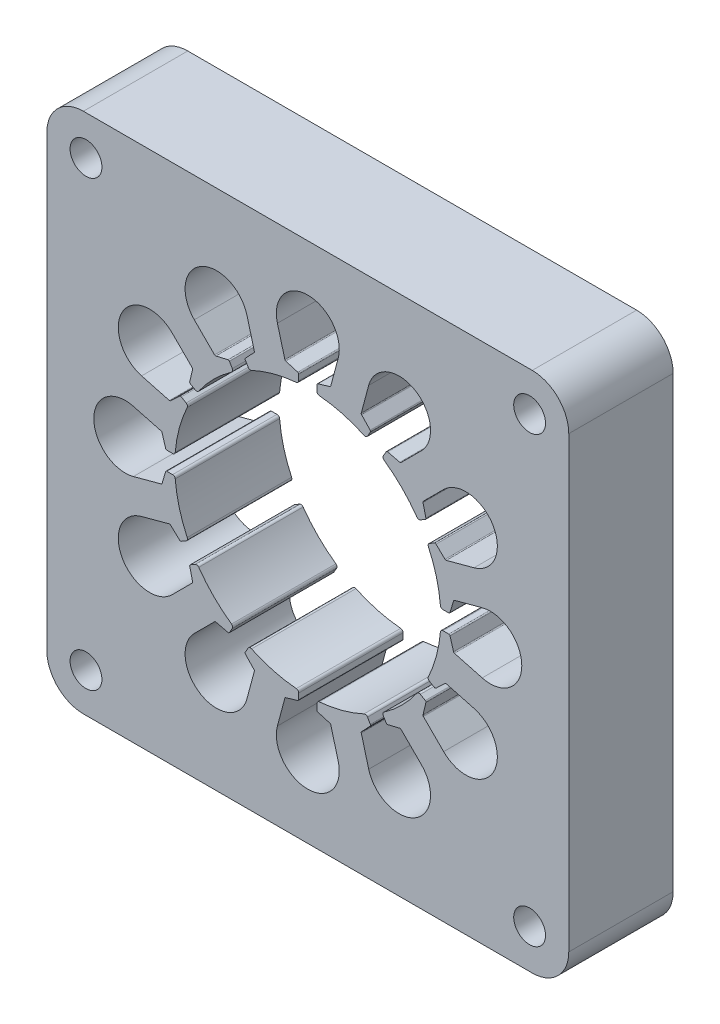
SolidWorks part; units mm, degrees
ref_plane "Front" through (0, 0, 0) normal (0, 0, 1) x (1, 0, 0)
ref_plane "Top" through (0, 0, 0) normal (0, 1, 0) x (1, 0, 0)
ref_plane "Right" through (0, 0, 0) normal (1, 0, 0) x (0, 0, -1)
sketch "Sketch1" plane through (0, 0, 0) normal (0, 0, 1) x (1, 0, 0)
  line L1 (0, 0) -> (100, 0)
  line L2 (0, 0) -> (0, 100)
  line L3 (0, 100) -> (100, 100)
  line L4 (100, 0) -> (100, 100)
  dimension "D1" = 100
extrude "Boss-Extrude1" add sketch "Sketch1" along normal blind 20
sketch "Sketch2" plane through (0, 0, 20) normal (0, 0, 1) x (1, 0, 0)
  line L0 (50, 100) -> (50, 50) construction
  line L1 (100, 100) -> (0, 100) construction
  line L2 (50, 50) -> (100, 50) construction
  line L3 (100, 0) -> (100, 100) construction
  circle A0 centre (50, 50) radius 25.5
  dimension "D1" = 51
extrude "Cut-Extrude1" cut sketch "Sketch2" against normal through all
sketch "Sketch3" plane through (0, 0, 20) normal (0, 0, 1) x (1, 0, 0)
  line L0 (48.25, 75.4399) -> (51.75, 75.4399) construction
  line L1 (50, 50) -> (36.6025, 100) construction
  line L2 (48.25, 75.4399) -> (48.25, 77.1899)
  line L3 (51.75, 75.4399) -> (51.75, 77.1899)
  line L4 (48.25, 77.1899) -> (51.75, 77.1899) construction
  line L5 (48.25, 77.1899) -> (45.6385, 77.9649)
  line L6 (44.1786, 83.4134) -> (45.6385, 77.9649)
  line L7 (54.3615, 77.9649) -> (51.75, 77.1899)
  line L8 (50, 50) -> (63.3975, 100) construction
  line L9 (50, 91) -> (50, 50) construction
  line L12 (50, 100) -> (50, 91) construction
  line L13 (100, 100) -> (0, 100) construction
  line L14 (55.8214, 83.4134) -> (54.3615, 77.9649)
  line L15 (45.6385, 77.9649) -> (54.3615, 77.9649) construction
  circle A0 centre (50, 50) radius 25.5 construction
  arc A1 (44.1786, 83.4134) -> (55.8214, 83.4134) centre (50, 84.9733) cw
  point P2 (50, 75.4399)
  dimension "D1" = 3.5
  dimension "D2" = 1.75
  dimension "D3" = 9
  dimension "D4" = 2.525
  dimension "D5" = 15
  dimension "D6" = 15
  dimension "D7" = 3.025
extrude "Cut-Extrude2" cut sketch "Sketch3" against normal through all and the other way through all
pattern_circular "CirPattern7" count 12 over 360 about axis through (50, 50, 20) along (0, 0, 1) of "Cut-Extrude2"
fillet "Fillet4" radius 0.2525 48 edges at (48.25, 77.1899, 10) (45.6385, 77.9649, 10) (51.75, 77.1899, 10) (54.3615, 77.9649, 10) (62.0794, 74.4221, 10) (60.2053, 76.399, 10) (65.1105, 72.6721, 10) (67.7596, 72.0376, 10) (72.6721, 65.1105, 10) (72.0376, 67.7596, 10) (74.4221, 62.0794, 10) (76.399, 60.2053, 10) (77.1899, 51.75, 10) (77.9649, 54.3615, 10) (77.1899, 48.25, 10) (77.9649, 45.6385, 10) (76.399, 39.7947, 10) (74.4221, 37.9206, 10) (72.6721, 34.8895, 10) (72.0376, 32.2404, 10) (67.7596, 27.9624, 10) (65.1105, 27.3279, 10) (62.0794, 25.5779, 10) (60.2053, 23.601, 10) (54.3615, 22.0351, 10) (51.75, 22.8101, 10) (48.25, 22.8101, 10) (45.6385, 22.0351, 10) (39.7947, 23.601, 10) (37.9206, 25.5779, 10) (34.8895, 27.3279, 10) (32.2404, 27.9624, 10) (27.3279, 34.8895, 10) (27.9624, 32.2404, 10) (25.5779, 37.9206, 10) (23.601, 39.7947, 10) (22.8101, 51.75, 10) (22.0351, 54.3615, 10) (22.8101, 48.25, 10) (22.0351, 45.6385, 10) (27.3279, 65.1105, 10) (27.9624, 67.7596, 10) (25.5779, 62.0794, 10) (34.8895, 72.6721, 10) (37.9206, 74.4221, 10) (39.7947, 76.399, 10) (23.601, 60.2053, 10) (32.2404, 72.0376, 10)
fillet "Fillet5" radius 0.505 24 edges at (48.25, 75.4399, 10) (38.7956, 72.9066, 10) (35.7645, 71.1566, 10) (28.8434, 64.2355, 10) (27.0934, 61.2044, 10) (24.5601, 51.75, 10) (24.5601, 48.25, 10) (27.0934, 38.7956, 10) (28.8434, 35.7645, 10) (35.7645, 28.8434, 10) (38.7956, 27.0934, 10) (48.25, 24.5601, 10) (51.75, 24.5601, 10) (61.2044, 27.0934, 10) (64.2355, 28.8434, 10) (71.1566, 35.7645, 10) (72.9066, 38.7956, 10) (75.4399, 48.25, 10) (75.4399, 51.75, 10) (72.9066, 61.2044, 10) (71.1566, 64.2355, 10) (64.2355, 71.1566, 10) (61.2044, 72.9066, 10) (51.75, 75.4399, 10)
sketch "Sketch4" plane through (0, 0, 20) normal (0, 0, 1) x (1, 0, 0)
  line L1 (7.5, 92.5) -> (92.5, 92.5) construction
  line L2 (7.5, 92.5) -> (7.5, 7.5) construction
  line L3 (7.5, 7.5) -> (92.5, 7.5) construction
  line L4 (92.5, 92.5) -> (92.5, 7.5) construction
  line L5 (7.5, 92.5) -> (92.5, 7.5) construction
  line L6 (7.5, 7.5) -> (92.5, 92.5) construction
  arc A0 (70.8949, 64.6169) -> (64.6169, 70.8949) centre (50, 50) ccw construction
  circle A1 centre (92.5, 92.5) radius 3.05
  circle A2 centre (92.5, 7.5) radius 3.05
  circle A3 centre (7.5, 7.5) radius 3.05
  circle A4 centre (7.5, 92.5) radius 3.05
  point P0 (50, 50)
  dimension "D2" = 6.1
  dimension "D1" = 85
extrude "Cut-Extrude3" cut sketch "Sketch4" against normal through all
fillet "Fillet7" radius 7 4 edges at (100, 0, 10) (0, 0, 10) (0, 100, 10) (100, 100, 10)
equation "\"OUTD\"= 100mm"
equation "\"GAP\"= 1mm"
equation "\"HEIGHT\"= 20mm"
equation "\"SLOTS\"= 12"
equation "\"SD1\"= \"OUTD\""
equation "\"SD2\"= 51mm"
equation "\"SW2\"= 3.5mm"
equation "\"SW4\"= 9mm"
equation "\"ST\"= 1.75mm"
equation "\"STD1\"= 2.525mm"
equation "\"SW1\"= 6.05mm"
equation "\"SF1\"= 0.2525mm"
equation "\"SF2\"= 1mm"
equation "\"D1@Sketch1\"=\"OUTD\""
equation "\"D1@Boss-Extrude1\"=\"HEIGHT\""
equation "\"D1@Sketch2\"=\"SD2\""
equation "\"D1@Sketch3\"=\"SW2\""
equation "\"D2@Sketch3\"=\"ST\""
equation "\"D3@Sketch3\"=\"SW4\""
equation "\"D7@Sketch3\"=\"SW1\"/2"
equation "\"D4@Sketch3\"=\"STD1\""
equation "\"D1@CirPattern7\"=\"SLOTS\""
equation "\"D1@Fillet4\"=\"SF1\""
equation "\"D1@Fillet5\"=\"SF1\"*2"
equation "\"D1@Sketch4\"=85mm"
